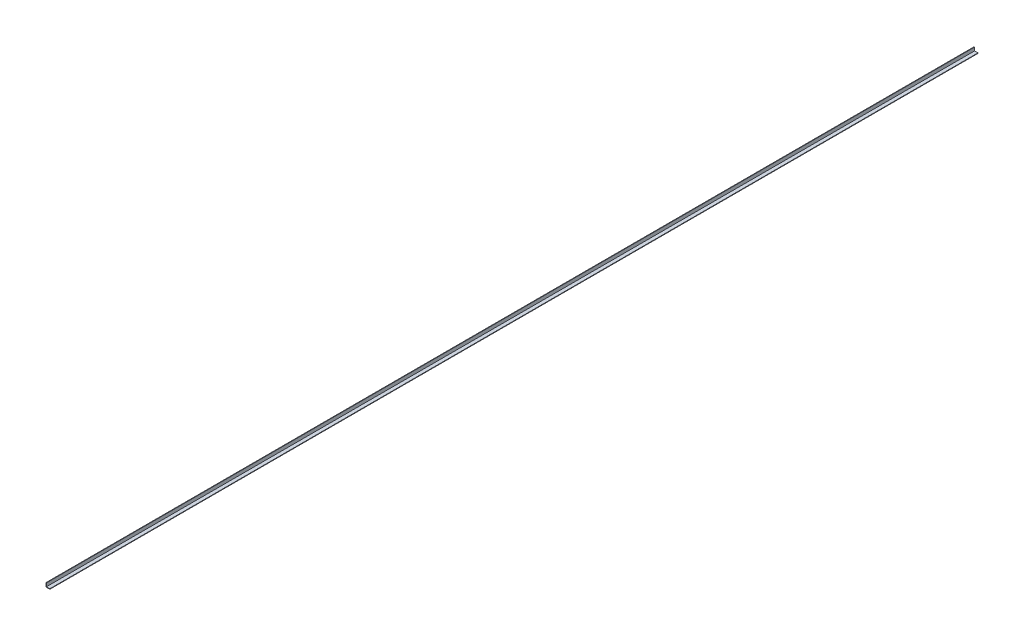
SolidWorks part; units mm, degrees
material "ASTM A36 Acero"
ref_plane "Alzado" through (0, 0, 0) normal (0, 0, 1) x (1, 0, 0)
ref_plane "Planta" through (0, 0, 0) normal (0, 1, 0) x (1, 0, 0)
ref_plane "Vista lateral" through (0, 0, 0) normal (1, 0, 0) x (0, 0, -1)
sketch "Croquis1" plane through (0, 0, 0) normal (0, 0, 1) x (1, 0, 0)
  line L0 (0, 25.4) -> (0, 0)
  line L1 (0, 0) -> (25.4, 0)
  line L2 (25.4, 0) -> (25.4, 3.18)
  line L3 (25.4, 3.18) -> (3.18, 3.18)
  line L4 (3.18, 3.18) -> (3.18, 25.4)
  line L5 (3.18, 25.4) -> (0, 25.4)
  dimension "D1" = 3.18
  dimension "D2" = 25.4
extrude "Saliente-Extruir1" add sketch "Croquis1" against normal blind 6100
